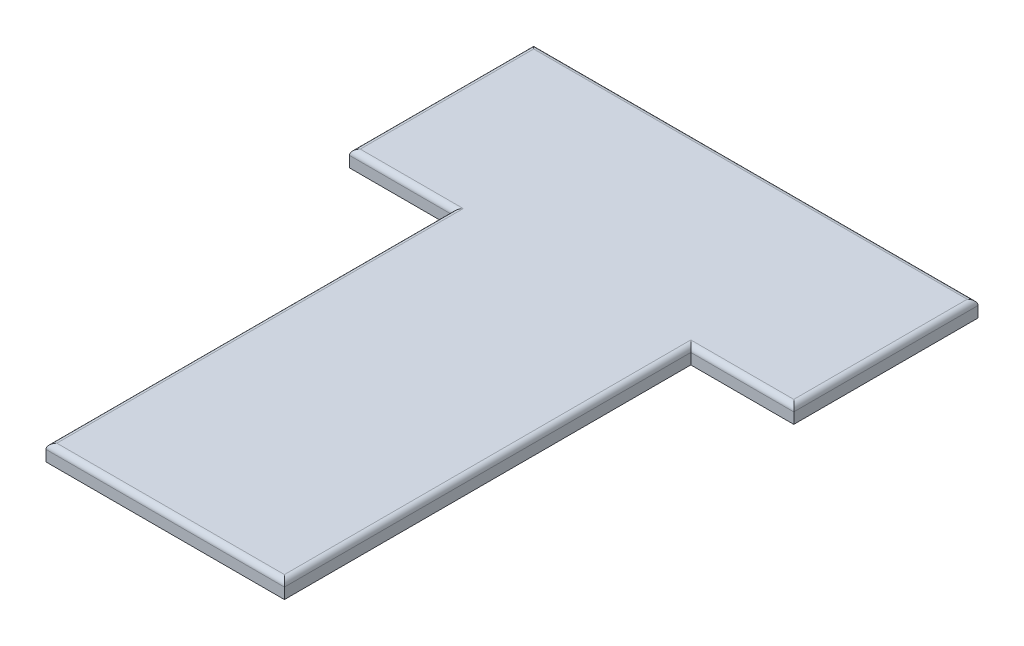
SolidWorks part; units mm, degrees
material "PF"
ref_plane "Front Plane" through (0, 0, 0) normal (0, 0, 1) x (1, 0, 0)
ref_plane "Top Plane" through (0, 0, 0) normal (0, 1, 0) x (1, 0, 0)
ref_plane "Right Plane" through (0, 0, 0) normal (1, 0, 0) x (0, 0, -1)
sketch "Sketch1" plane through (0, 0, 0) normal (0, 1, 0) x (1, 0, 0)
  line L0 (0, 0) -> (19, 0) construction
  line L1 (19, 0) -> (19, 75)
  line L2 (19, 75) -> (0, 75)
  line L3 (0, 75) -> (0, 109)
  line L4 (0, 109) -> (82, 109)
  line L5 (82, 109) -> (82, 75)
  line L6 (82, 75) -> (63, 75)
  line L7 (63, 75) -> (63, 0)
  line L8 (63, 0) -> (19, 0)
  dimension "D1" = 19
  dimension "D2" = 75
  dimension "D3" = 82
  dimension "D4" = 34
extrude "Boss-Extrude1" add sketch "Sketch1" along normal blind 3
fillet "Fillet2" radius 1 8 edges at (41, 3, -109) (82, 3, -92) (72.5, 3, -75) (63, 3, -37.5) (41, 3, 0) (19, 3, -37.5) (9.5, 3, -75) (0, 3, -92)
sketch "Sketch3" plane through (0, 3, 0) normal (0, 1, 0) x (1, 0, 0)
  line L0 (41, 108) -> (41, 0) construction
  line L1 (1, 106) -> (81, 106)
  line L2 (1, 106) -> (1, 70)
  line L3 (1, 70) -> (81, 70)
  line L4 (81, 106) -> (81, 70)
  line L5 (1, 106) -> (81, 70) construction
  line L6 (1, 70) -> (81, 106) construction
  line L7 (81, 108) -> (1, 108) construction
  line L8 (19, 0) -> (63, 0) construction
  line L9 (19, 75) -> (0, 75) construction
  line L10 (17.5, 63.9723) -> (64.5, 63.9723)
  line L11 (17.5, 63.9723) -> (17.5, 11.6563)
  line L12 (17.5, 11.6563) -> (64.5, 11.6563)
  line L13 (64.5, 63.9723) -> (64.5, 11.6563)
  line L14 (17.5, 63.9723) -> (64.5, 11.6563) construction
  line L15 (17.5, 11.6563) -> (64.5, 63.9723) construction
  point P0 (41, 88)
  point P12 (41, 37.8143)
  dimension "D1" = 36
  dimension "D2" = 80
  dimension "D3" = 2
  dimension "D4" = 47
  dimension "D5" = 52.3159
  dimension "D6" = 11.0277
